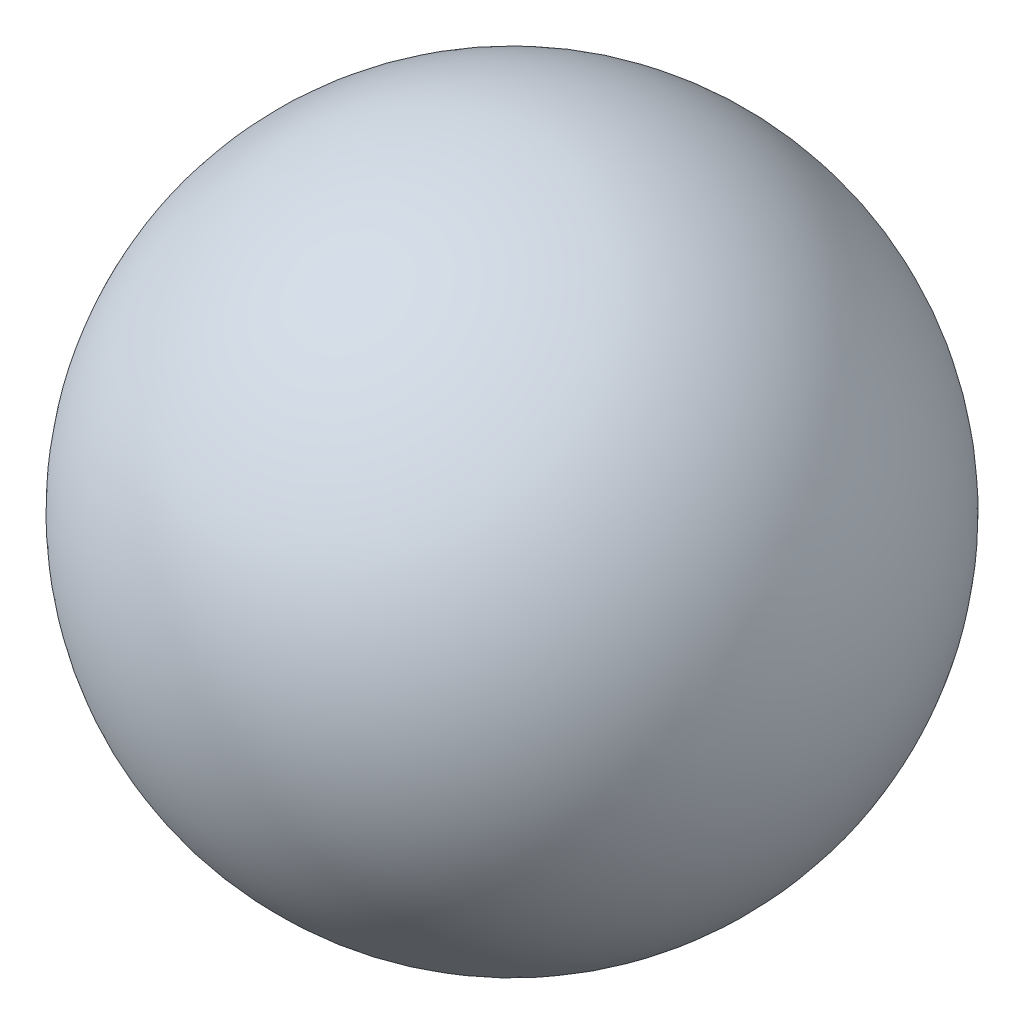
SolidWorks part; units mm, degrees
ref_plane "Front Plane" through (0, 0, 0) normal (0, 0, 1) x (1, 0, 0)
ref_plane "Top Plane" through (0, 0, 0) normal (0, 1, 0) x (1, 0, 0)
ref_plane "Right Plane" through (0, 0, 0) normal (1, 0, 0) x (0, 0, -1)
sketch "Sketch1" plane through (0, 0, 0) normal (0, 1, 0) x (1, 0, 0)
  line L0 (-50.8, 0) -> (50.8, 0)
  arc A0 (50.8, 0) -> (-50.8, 0) centre (0, 0) ccw
revolve "Revolve1" add sketch "Sketch1" angle 360 about L0
